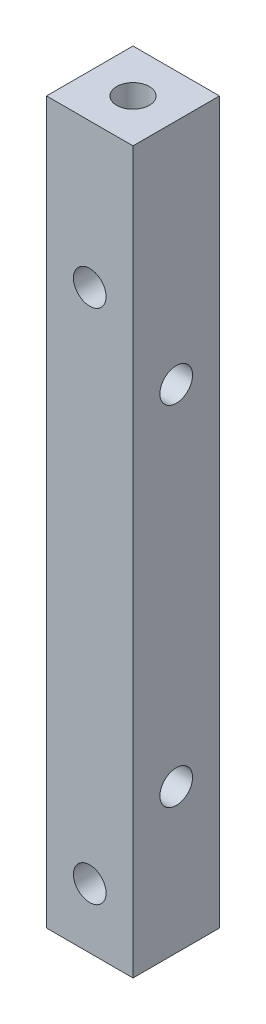
SolidWorks part; units mm, degrees
material "6061-T6 (SS)"
ref_plane "Front Plane" through (0, 0, 0) normal (0, 0, 1) x (1, 0, 0)
ref_plane "Top Plane" through (0, 0, 0) normal (0, 1, 0) x (1, 0, 0)
ref_plane "Right Plane" through (0, 0, 0) normal (1, 0, 0) x (0, 0, -1)
sketch "Sketch1" plane through (0, 0, 0) normal (0, 1, 0) x (1, 0, 0)
  line L1 (-4.572, 4.572) -> (4.572, 4.572)
  line L2 (-4.572, 4.572) -> (-4.572, -4.572)
  line L3 (-4.572, -4.572) -> (4.572, -4.572)
  line L4 (4.572, 4.572) -> (4.572, -4.572)
  line L5 (-4.572, 4.572) -> (4.572, -4.572) construction
  line L6 (-4.572, -4.572) -> (4.572, 4.572) construction
  point P0 (0, 0)
  dimension "D1" = 9.144
extrude "Boss-Extrude1" add sketch "Sketch1" along normal blind 76.2
sketch "Sketch3" plane through (0, 0, 4.572) normal (0, 0, 1) x (1, 0, 0)
  line L0 (0, 60.96) -> (0, 6.35) construction
  line L1 (4.572, 76.2) -> (4.572, 0) construction
  line L2 (-4.572, 0) -> (4.572, 0) construction
  line L3 (-4.572, 76.2) -> (4.572, 76.2) construction
  point P3 (0, 33.655)
  point P6 (0, 65.084)
  point P8 (4.572, 38.1)
  point P12 (0, 0)
  dimension "D1" = 6.35
  dimension "D2" = 15.24
hole_wizard "Tap Drill for #8-32 Tap1" positions "Sketch4" profile "Sketch6" hole size "#8-32" standard "ANSI Inch" end condition through all
sketch "Sketch4" plane through (0, 0, 4.572) normal (0, 0, 1) x (1, 0, 0)
  point P0 (0, 60.96)
  point P3 (0, 6.35)
sketch "Sketch6" plane through (0, 60.96, 4.572) normal (1, 0, 0) x (0, -1, 0)
  line L0 (0, 0) -> (0, 9.144)
  line L1 (0, 9.144) -> (1.7272, 9.144)
  line L2 (1.7272, 9.144) -> (1.7272, 0)
  line L5 (1.7272, 0) -> (0, 0)
  line L11 (0, -6.35) -> (0, 107.95) construction
  dimension "Thru Hole Dia." = 3.4544
  dimension "Thru Hole Depth" = 9.144
sketch "Sketch7" plane through (4.572, 0, 0) normal (1, 0, 0) x (0, 0, -1)
  line L0 (0, 52.07) -> (0, 15.24) construction
  line L2 (-4.572, 0) -> (4.572, 0) construction
  point P2 (0, 0)
  point P3 (0, 33.655)
  point P6 (0, 0)
  point P8 (0, 0)
  dimension "D1" = 36.83
hole_wizard "Tap Drill for #8-32 Tap2" positions "Sketch10" profile "Sketch11" hole size "#8-32" standard "ANSI Inch" end condition through all
sketch "Sketch10" plane through (4.572, 0, 0) normal (1, 0, 0) x (0, 0, -1)
  point P0 (0, 52.07)
  point P3 (0, 15.24)
sketch "Sketch11" plane through (4.572, 52.07, 0) normal (0, 1, 0) x (0, 0, -1)
  line L0 (0, 0) -> (0, 9.144)
  line L1 (0, 9.144) -> (1.7272, 9.144)
  line L2 (1.7272, 9.144) -> (1.7272, 0)
  line L5 (1.7272, 0) -> (0, 0)
  line L11 (0, -6.35) -> (0, 107.95) construction
  dimension "Thru Hole Dia." = 3.4544
  dimension "Thru Hole Depth" = 9.144
hole_wizard "Tap Drill for #8-32 Tap3" positions "Sketch13" profile "Sketch15" hole size "#8-32" standard "ANSI Inch"
sketch "Sketch13" plane through (0, 76.2, 0) normal (0, 1, 0) x (1, 0, 0)
  point P0 (0, 0)
sketch "Sketch15" plane through (0, 76.2, 0) normal (1, 0, 0) x (0, 0, 1)
  line L0 (0, 0) -> (0, 8.6578)
  line L1 (0, 8.6578) -> (1.7272, 7.62)
  line L2 (1.7272, 7.62) -> (1.7272, 0)
  line L5 (1.7272, 0) -> (0, 0)
  line L10 (0, 8.6578) -> (-1.7272, 7.62) construction
  line L11 (0, -6.35) -> (0, 107.95) construction
  dimension "Hole Dia." = 3.4544
  dimension "Hole Depth" = 7.62
  dimension "Drill Angle" = 118
